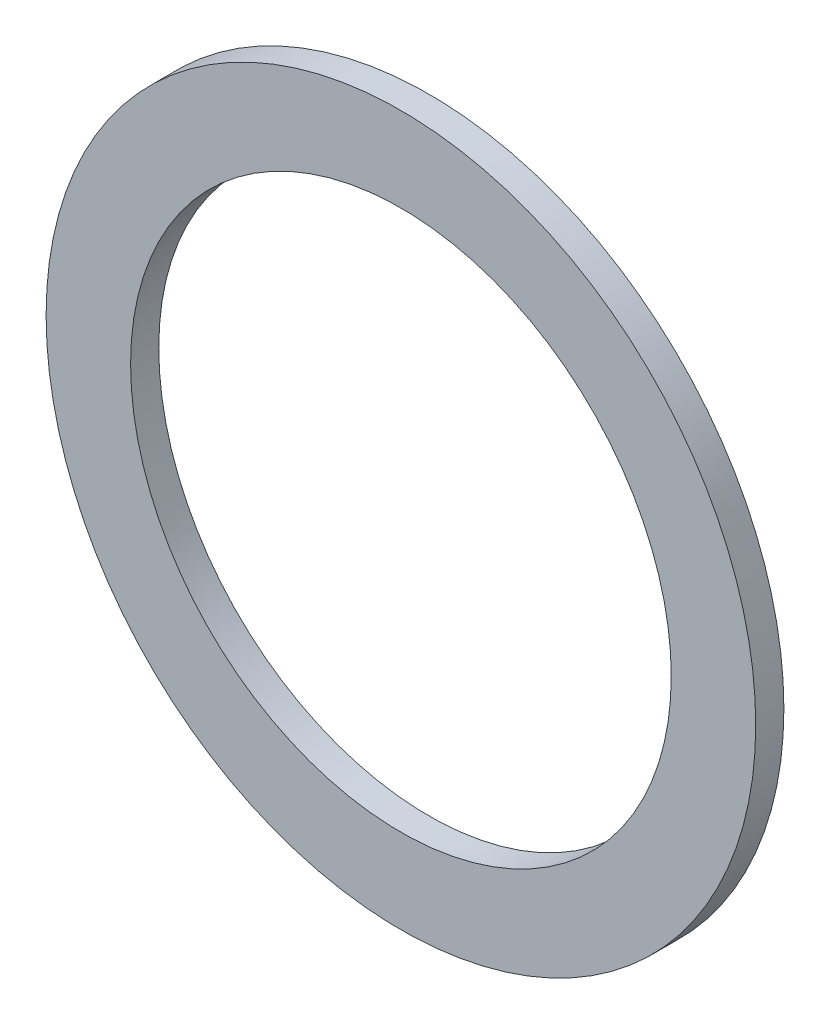
SolidWorks part; units mm, degrees
ref_plane "Спереди" through (0, 0, 0) normal (0, 0, 1) x (1, 0, 0)
ref_plane "Сверху" through (0, 0, 0) normal (0, 1, 0) x (1, 0, 0)
ref_plane "Справа" through (0, 0, 0) normal (1, 0, 0) x (0, 0, -1)
sketch "Эскиз1" plane through (0, 0, 0) normal (0, 0, 1) x (1, 0, 0)
  circle A0 centre (0, 0) radius 4.8
  circle A1 centre (0, 0) radius 6.3
  dimension "D1" = 9.6
  dimension "D2" = 12.6
extrude "Вытянуть1" add sketch "Эскиз1" along normal blind 0.5
